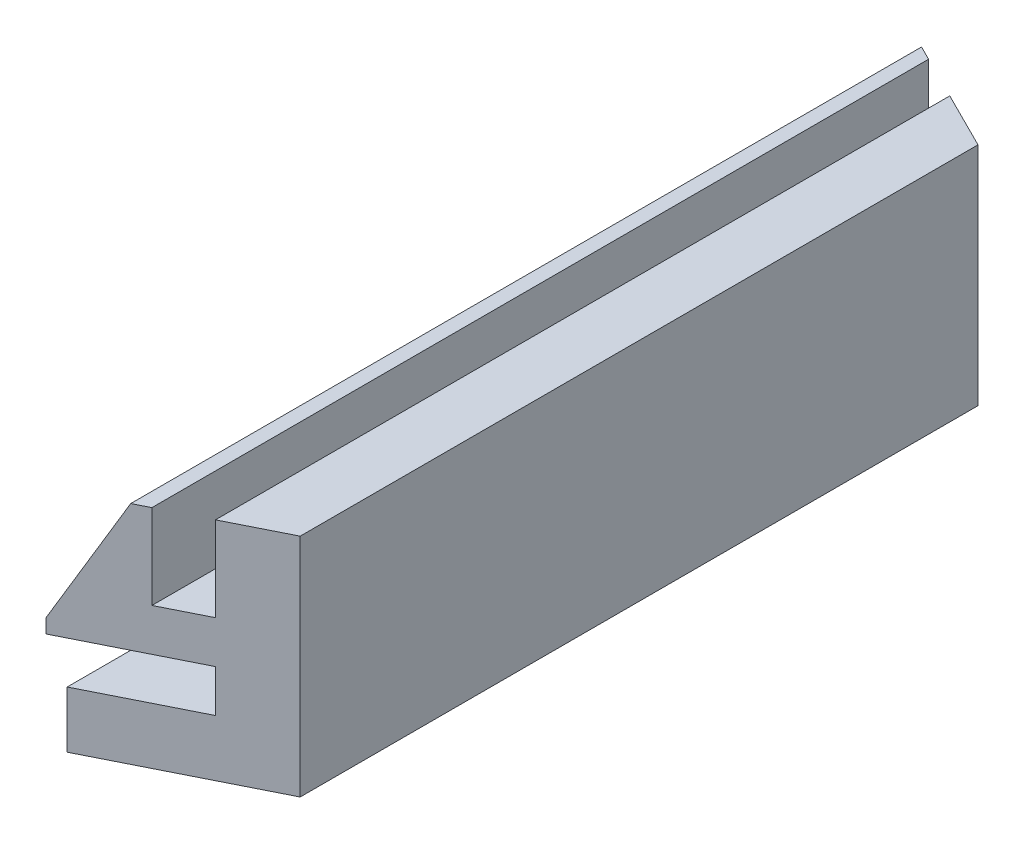
SolidWorks part; units mm, degrees
material "ABS"
ref_plane "Płaszczyzna przednia" through (0, 0, 0) normal (0, 0, 1) x (1, 0, 0)
ref_plane "Płaszczyzna górna" through (0, 0, 0) normal (0, 1, 0) x (1, 0, 0)
ref_plane "Płaszczyzna prawa" through (0, 0, 0) normal (1, 0, 0) x (0, 0, -1)
sketch "Szkic1" plane through (0, 0, 0) normal (0, 0, 1) x (1, 0, 0)
  line L0 (0, 0) -> (-7, 0)
  line L1 (-7, 0) -> (-7, -4)
  line L2 (-7, -4) -> (-0.5068, -4)
  line L3 (0, 0) -> (0, 3)
  line L4 (0, 3) -> (-8, 3)
  line L5 (-8, 3) -> (-8, 4)
  line L6 (-0.5068, -4) -> (4, -4)
  line L7 (4, -4) -> (4, 12)
  line L8 (4, 12) -> (0, 12)
  line L9 (0, 12) -> (0, 6)
  line L10 (0, 6) -> (-3, 6)
  line L11 (-3, 6) -> (-3, 12)
  line L12 (-3, 12) -> (-4, 12)
  line L13 (-4, 12) -> (-8, 4)
  dimension "D1" = 4
  dimension "D2" = 3
  dimension "D3" = 1
  dimension "D4" = 3
  dimension "D5" = 4
  dimension "D6" = 1
  dimension "D7" = 7
  dimension "D8" = 8
  dimension "D9" = 16
  dimension "D10" = 3
extrude "Dodanie-wyciągnięcie1" add sketch "Szkic1" along normal blind 70
sketch "Szkic2" plane through (0, 12, 0) normal (0, 1, 0) x (1, 0, 0)
  line L0 (-15.9242, -0.2668) -> (4, -10.2311)
  line L1 (-15.9242, -68.1953) -> (4, -58.2311)
  line L2 (4, -58.2311) -> (4, -10.2311)
  line L3 (-15.9242, -0.2668) -> (-15.9242, -68.1953)
  line L4 (4, -70) -> (4, 0) construction
  line L5 (-8, -70) -> (-8, 0) construction
  line L6 (-8, -70) -> (-8, 0)
  point P6 (10.5079, -19.3652)
  point P7 (9.0815, -8.3933)
  point P10 (9.602, -10.2311)
  line M6 (0, 0) -> (0, -70)
  line M8 (4, -70) -> (4, 0)
  dimension "D1" = 48
  dimension "D2" = 116.57
extrude "Wytnij-wyciągnięcie1" cut sketch "Szkic2" against normal through all flip side to cut contours L1 L0 M6 M8 | L6 L1 L0 M6
